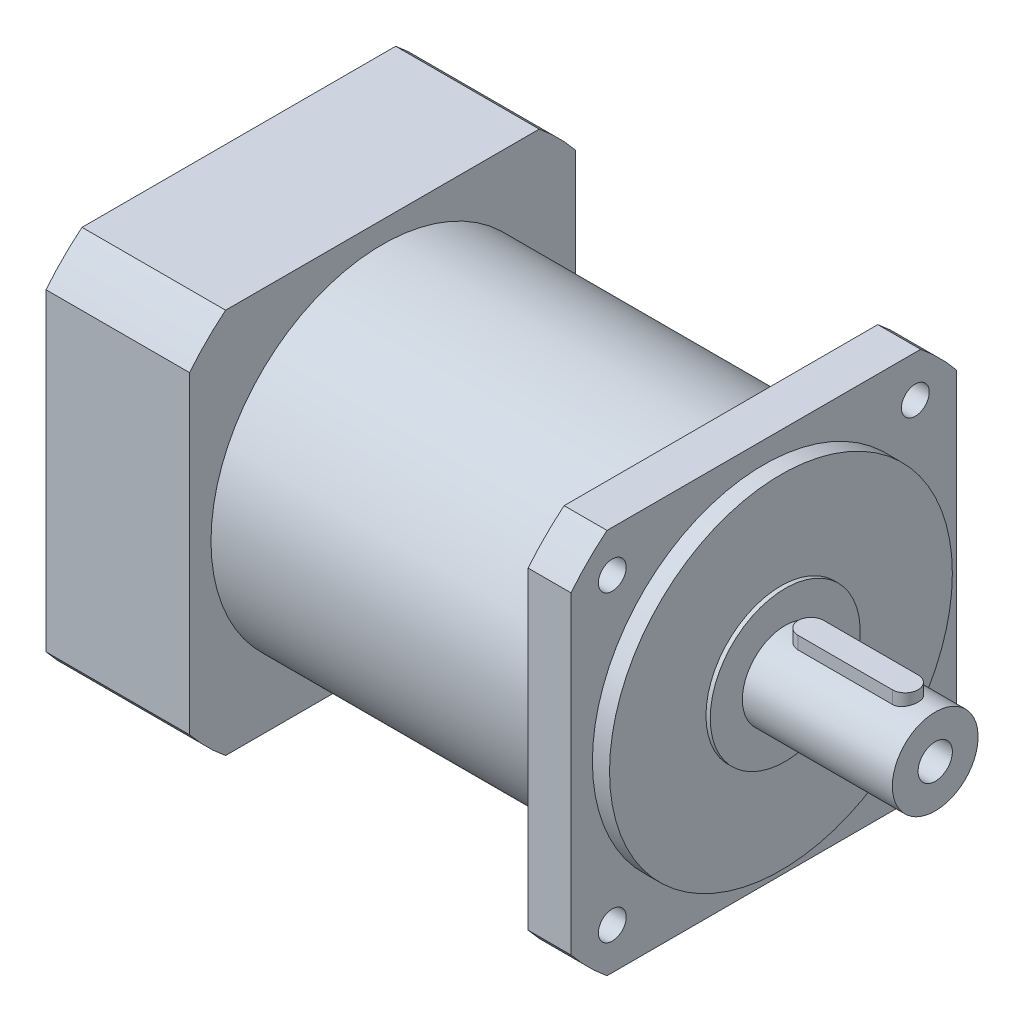
SolidWorks part; units mm, degrees
ref_plane "前视基准面" through (0, 0, 0) normal (0, 0, 1) x (1, 0, 0)
ref_plane "上视基准面" through (0, 0, 0) normal (0, 1, 0) x (1, 0, 0)
ref_plane "右视基准面" through (0, 0, 0) normal (1, 0, 0) x (0, 0, -1)
sketch "草图1" plane through (0, 0, 0) normal (0, 0, 1) x (1, 0, 0)
  line L0 (-53.5264, 0) -> (59.0316, 0) construction
  line L1 (0, 62.6082) -> (0, -76.2931) construction
  line L2 (0, 0) -> (0, 40)
  line L3 (0, 40) -> (4, 40)
  line L4 (4, 40) -> (4, 17.5)
  line L5 (4, 17.5) -> (5, 17.5)
  line L6 (5, 17.5) -> (5, 10)
  line L7 (5, 10) -> (40, 10)
  line L8 (40, 10) -> (40, 0)
  line L9 (40, 0) -> (0, 0)
  dimension "D1" = 40
  dimension "D2" = 36
  dimension "D3" = 40
  dimension "D4" = 17.5
  dimension "D5" = 10
  dimension "D6" = 1
revolve "旋转1" add sketch "草图1" angle 360 about L0
sketch "草图2" plane through (0, 0, 0) normal (0, 1, 0) x (1, 0, 0)
  line L0 (-5.0581, 0) -> (43.1806, 0) construction
  line L1 (11, 0) -> (33, 0) construction
  line L2 (11, 3) -> (33, 3)
  line L3 (11, -3) -> (33, -3)
  line L4 (40, -10) -> (40, 10) construction
  arc A0 (11, 3) -> (11, -3) centre (11, 0) ccw
  arc A1 (33, -3) -> (33, 3) centre (33, 0) ccw
  point P5 (22, 0)
  point P10 (36, 0)
  point P13 (8, 0)
  dimension "D1" = 6
  dimension "D2" = 4
  dimension "D3" = 28
extrude "凸台-拉伸1" add sketch "草图2" along normal blind 12.5
sketch "草图3" plane through (40, 0, 0) normal (1, 0, 0) x (0, 0, -1)
  circle A0 centre (0, 0) radius 4
  dimension "D1" = 8
extrude "切除-拉伸1" cut sketch "草图3" against normal up to next
sketch "草图4" plane through (0, 0, 0) normal (-1, 0, 0) x (0, 0, 1)
  line L0 (-32.8536, 0) -> (21.2934, 0) construction
  line L1 (36.5923, -45) -> (-36.5923, -45)
  line L2 (45, -36.5923) -> (45, 36.5923)
  line L3 (36.5923, 45) -> (-36.5923, 45)
  line L4 (-45, -36.5923) -> (-45, 36.5923)
  line L5 (45, -45) -> (-45, 45) construction
  line L6 (45, 45) -> (-45, -45) construction
  arc A0 (-45, -36.5923) -> (-36.5923, -45) centre (0, 0) ccw
  arc A1 (-36.5923, 45) -> (-45, 36.5923) centre (0, 0) ccw
  arc A2 (45, 36.5923) -> (36.5923, 45) centre (0, 0) ccw
  arc A3 (36.5923, -45) -> (45, -36.5923) centre (0, 0) ccw
  circle A4 centre (0, 0) radius 50 construction
  circle A5 centre (-35.3553, 35.3553) radius 3.25
  circle A6 centre (35.3553, -35.3553) radius 3.25
  circle A7 centre (35.3553, 35.3553) radius 3.25
  circle A8 centre (-35.3553, -35.3553) radius 3.25
  point P0 (0, 0)
  dimension "D3" = 116
  dimension "D4" = 90
  dimension "D8" = 100
  dimension "D9" = 6.5
  dimension "D1" = 90
  dimension "D2" = 90
  dimension "D5" = 90
  dimension "D6" = 45
  dimension "D7" = 45
extrude "凸台-拉伸2" add sketch "草图4" along normal blind 10
sketch "草图5" plane through (-10, 0, 0) normal (-1, 0, 0) x (0, 0, 1)
  circle A0 centre (0, 0) radius 40
  dimension "D1" = 80
extrude "凸台-拉伸3" add sketch "草图5" along normal blind 79
sketch "草图6" plane through (-89, 0, 0) normal (-1, 0, 0) x (0, 0, 1)
  line L4 (36.5923, 45) -> (-36.5923, 45)
  line L5 (-45, 36.5923) -> (-45, -36.5923)
  line L6 (-36.5923, -45) -> (36.5923, -45)
  line L7 (45, -36.5923) -> (45, 36.5923)
  line L8 (36.5923, 45) -> (-36.5923, 45)
  line L9 (-45, 36.5923) -> (-45, -36.5923)
  line L10 (-36.5923, -45) -> (36.5923, -45)
  line L11 (45, -36.5923) -> (45, 36.5923)
  arc A4 (45, 36.5923) -> (36.5923, 45) centre (0, 0) ccw
  arc A5 (-36.5923, 45) -> (-45, 36.5923) centre (0, 0) ccw
  arc A6 (-45, -36.5923) -> (-36.5923, -45) centre (0, 0) ccw
  arc A7 (36.5923, -45) -> (45, -36.5923) centre (0, 0) ccw
  arc A8 (45, 36.5923) -> (36.5923, 45) centre (0, 0) ccw
  arc A9 (-36.5923, 45) -> (-45, 36.5923) centre (0, 0) ccw
  arc A10 (-45, -36.5923) -> (-36.5923, -45) centre (0, 0) ccw
  arc A11 (36.5923, -45) -> (45, -36.5923) centre (0, 0) ccw
  dimension "D1" = 0
extrude "凸台-拉伸4" add sketch "草图6" along normal blind 33.5
sketch "草图7" plane through (-122.5, 0, 0) normal (-1, 0, 0) x (0, 0, 1)
  circle A0 centre (0, 0) radius 40
  dimension "D1" = 80
extrude "切除-拉伸2" cut sketch "草图7" against normal blind 3.5
sketch "草图8" plane through (-122.5, 0, 0) normal (-1, 0, 0) x (0, 0, 1)
  circle A0 centre (0, 0) radius 7
  dimension "D1" = 14
extrude "切除-拉伸3" cut sketch "草图8" against normal blind 30
sketch "草图9" plane through (-122.5, 0, 0) normal (-1, 0, 0) x (0, 0, 1)
  line L0 (0, 0) -> (47.8229, 47.8229) construction
  line L1 (0, 0) -> (-45.6997, 45.6997) construction
  line L2 (-21.0526, 0) -> (16.4453, 0) construction
  line L3 (0, 13.5789) -> (0, -15.239) construction
  circle A0 centre (0, 0) radius 50 construction
  circle A1 centre (35.3553, 35.3553) radius 3
  circle A2 centre (-35.3553, 35.3553) radius 3
  circle A3 centre (35.3553, -35.3553) radius 3
  circle A4 centre (-35.3553, -35.3553) radius 3
  dimension "D1" = 100
  dimension "D2" = 6
extrude "切除-拉伸4" cut sketch "草图9" against normal blind 15
